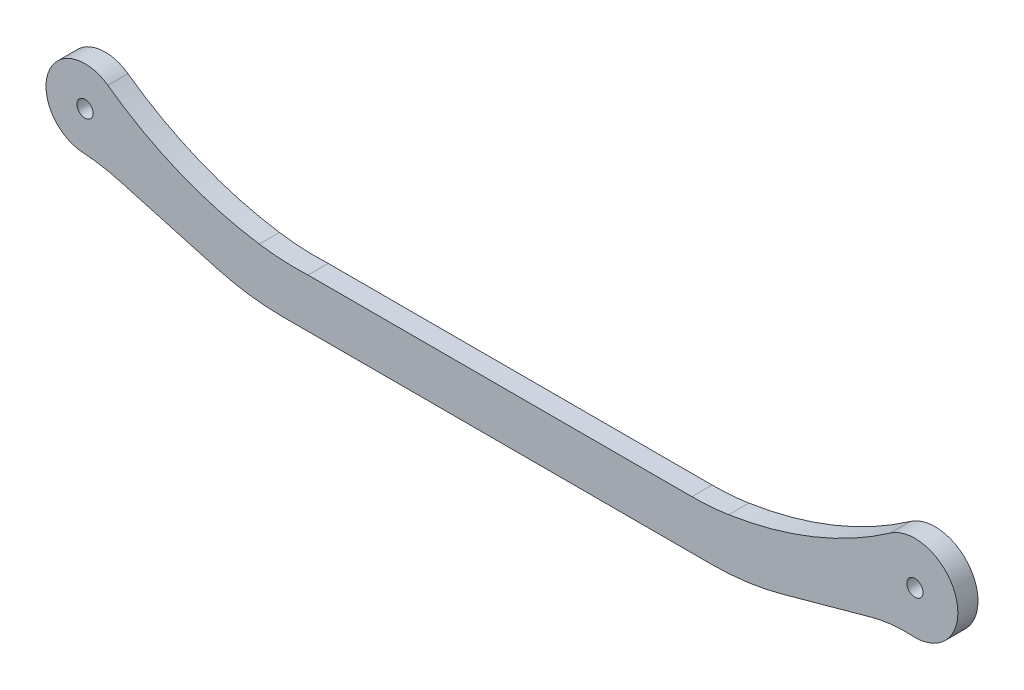
SolidWorks part; units mm, degrees
ref_plane "Front Plane" through (0, 0, 0) normal (0, 0, 1) x (1, 0, 0)
ref_plane "Top Plane" through (0, 0, 0) normal (0, 1, 0) x (1, 0, 0)
ref_plane "Right Plane" through (0, 0, 0) normal (1, 0, 0) x (0, 0, -1)
sketch "Sketch1" plane through (0, 0, 0) normal (0, 0, 1) x (1, 0, 0)
  line L2 (-116.9384, -13.9116) -> (-87, -22.25)
  line L3 (-66.8769, -25) -> (65, -25)
  line L4 (86.7565, -22.0613) -> (114.2351, -14.5)
  line L11 (59, -10) -> (-59, -10)
  line L18 (-127.575, 0) -> (127.575, 0) construction
  circle A0 centre (127.575, 0) radius 2.5
  circle A1 centre (-127.575, 0) radius 2.5
  arc A3 (-120.5545, 9.7321) -> (-128.3494, -11.975) centre (-127.575, 0) ccw
  arc A4 (-116.9384, -13.9116) -> (-128.3494, -11.975) centre (-131.9636, -67.8582) ccw
  arc A5 (-87, -22.25) -> (-66.8769, -25) centre (-66.8769, 50) ccw
  arc A6 (65, -25) -> (86.7565, -22.0613) centre (65, 57.0047) ccw
  arc A8 (126.8, -13.1772) -> (120, 10.8102) centre (127.575, 0) ccw
  arc A10 (59, -10) -> (70.3289, -9.1348) centre (59, 64.6) ccw
  arc A11 (-74, -9.25) -> (-59, -10) centre (-62.741, 65.5556) ccw
  arc A22 (-120.5545, 9.7321) -> (-74, -9.25) centre (-58.1155, 96.2872) ccw
  arc A25 (114.2351, -14.5) -> (126.8, -13.1772) centre (124.5233, -51.8885) cw
  arc A26 (70.3289, -9.1348) -> (120, 10.8102) centre (52.4542, 107.2039) ccw
  dimension "D1" = 127.575
  dimension "D2" = 5
  dimension "D5" = 12
  dimension "D7" = 59
  dimension "D9" = 9.25
  dimension "D10" = 75.6482
  dimension "D12" = 75
  dimension "D14" = 56
  dimension "D15" = 74.6
  dimension "D17" = 126.8
  dimension "D18" = 13.2
  dimension "D3" = 10
  dimension "D4" = 15
  dimension "D6" = 59
  dimension "D8" = 74
  dimension "D11" = 22.25
  dimension "D13" = 87
  dimension "D16" = 120
  dimension "D19" = 28.5
  dimension "D20" = 14.5
  dimension "D21" = 65
extrude "Boss-Extrude1" add sketch "Sketch1" along normal blind 6.2
